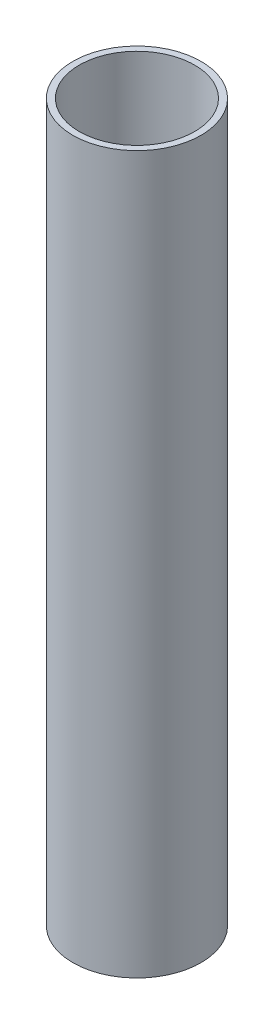
SolidWorks part; units mm, degrees
ref_plane "Front Plane" through (0, 0, 0) normal (0, 0, 1) x (1, 0, 0)
ref_plane "Top Plane" through (0, 0, 0) normal (0, 1, 0) x (1, 0, 0)
ref_plane "Right Plane" through (0, 0, 0) normal (1, 0, 0) x (0, 0, -1)
sketch "Sketch1" plane through (0, 0, 0) normal (0, 1, 0) x (1, 0, 0)
  circle A0 centre (0, 0) radius 10
  circle A1 centre (0, 0) radius 9
extrude "Boss-Extrude1" add sketch "Sketch1" along normal blind 111.8
